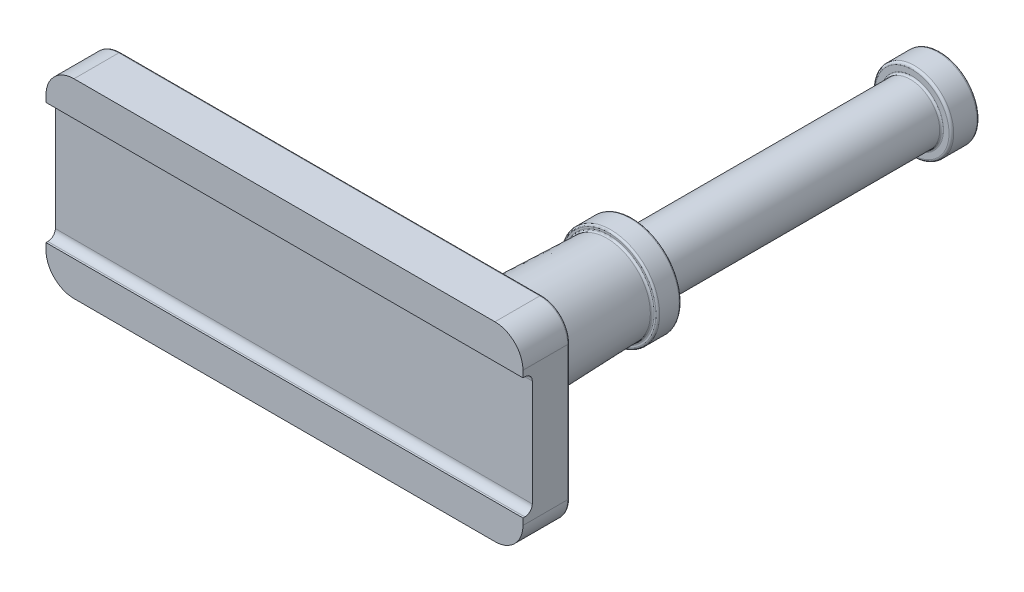
SolidWorks part; units mm, degrees
ref_plane "前视基准面" through (0, 0, 0) normal (0, 0, 1) x (1, 0, 0)
ref_plane "上视基准面" through (0, 0, 0) normal (0, 1, 0) x (1, 0, 0)
ref_plane "右视基准面" through (0, 0, 0) normal (1, 0, 0) x (0, 0, -1)
sketch "Sketch1" plane through (0, 0, 0) normal (0, 0, 1) x (1, 0, 0)
  line L1 (-1277.5, -510) -> (1277.5, -510)
  line L2 (-1277.5, -510) -> (-1277.5, 510)
  line L3 (-1277.5, 510) -> (1277.5, 510)
  line L4 (1277.5, -510) -> (1277.5, 510)
  line L5 (-1277.5, -510) -> (1277.5, 510) construction
  line L6 (-1277.5, 510) -> (1277.5, -510) construction
  point P0 (0, 0)
  dimension "D1" = 2555
  dimension "D2" = 1020
extrude "Extrude1" add sketch "Sketch1" along normal blind 250
fillet "Fillet1" radius 150 4 edges at (1277.5, -510, 125) (-1277.5, -510, 125) (1277.5, 510, 125) (-1277.5, 510, 125)
ref_plane "Plane1" through (762.5, 0, 0) normal (1, 0, 0) x (0, 0, -1)
sketch "Sketch4" plane through (762.5, 0, 0) normal (1, 0, 0) x (0, 0, -1)
  line L0 (0, 0) -> (2500, 0)
  line L1 (0, -360) -> (0, 360) construction
  line L2 (2500, 0) -> (2500, 210)
  line L3 (2500, 210) -> (2350, 210)
  line L4 (2350, 210) -> (2350, 157.5)
  line L5 (2350, 157.5) -> (850, 157.5)
  line L6 (850, 157.5) -> (850, 262.5)
  line L7 (850, 262.5) -> (725, 262.5)
  line L8 (725, 262.5) -> (725, 232.5)
  line L9 (725, 232.5) -> (80, 255.0239)
  line L10 (80, 255.0239) -> (80, 300)
  line L11 (80, 300) -> (0, 300)
  line L12 (0, 300) -> (0, 0)
  line L13 (2500, 0) -> (2810.0618, 0) construction
  dimension "D1" = 2500
  dimension "D2" = 150
  dimension "D3" = 1500
  dimension "D4" = 420
  dimension "D5" = 315
  dimension "D6" = 525
  dimension "D7" = 125
  dimension "D8" = 2
  dimension "D9" = 80
  dimension "D10" = 600
  dimension "D11" = 30
revolve "Revolve1" add sketch "Sketch4" angle 360 about L13
fillet "Fillet2" radius 10 8 edges at (920, 0, -2350) (920, 0, -850) (995, 0, -725) (1025, 0, -725) (1025, 0, -850) (1017.5239, 0, -80) (1062.5, 0, -80) (1062.5, 0, 0)
sketch "Sketch5" plane through (0, 0, 0) normal (0, 0, -1) x (-1, 0, 0)
  line L1 (1127.5, 395) -> (1127.5, 315)
  line L2 (1127.5, 315) -> (1072.5, 260)
  line L3 (1072.5, 260) -> (-290, 260)
  line L4 (-290, 260) -> (-302.5, 272.5)
  line L5 (-302.5, 272.5) -> (-382.5, 272.5)
  line L6 (-382.5, 272.5) -> (-382.5, 222.5)
  line L7 (-382.5, 222.5) -> (-302.5, 222.5)
  line L8 (-302.5, 222.5) -> (-290, 235)
  line L9 (-427.5, 420) -> (-427.5, -420) construction
  line L10 (-1277.5, -360) -> (-1277.5, 360) construction
  line L11 (-290, 235) -> (1072.5, 235)
  line L12 (1127.5, -420) -> (-1127.5, -420)
  line L13 (1187.5, 360) -> (1187.5, -360)
  line L14 (-1127.5, 420) -> (1127.5, 420)
  line L15 (1127.5, -420) -> (-382.5, -420)
  line L16 (1187.5, 360) -> (1187.5, -360)
  line L17 (-382.5, 420) -> (1127.5, 420)
  line L18 (1072.5, 235) -> (1072.5, 95)
  line L19 (1072.5, 95) -> (-290, 95)
  line L20 (-290, 95) -> (-302.5, 107.5)
  line L21 (-302.5, 107.5) -> (-382.5, 107.5)
  line L22 (-382.5, 107.5) -> (-382.5, 57.5)
  line L23 (-382.5, 57.5) -> (-302.5, 57.5)
  line L24 (-302.5, 57.5) -> (-290, 70)
  line L25 (-290, 70) -> (1072.5, 70)
  line L26 (1072.5, 70) -> (1072.5, -70)
  line L27 (1072.5, -70) -> (-290, -70)
  line L28 (-290, -70) -> (-302.5, -57.5)
  line L29 (-302.5, -57.5) -> (-382.5, -57.5)
  line L30 (-382.5, -57.5) -> (-382.5, -107.5)
  line L31 (-382.5, -107.5) -> (-302.5, -107.5)
  line L32 (-302.5, -107.5) -> (-290, -95)
  line L33 (-290, -95) -> (1072.5, -95)
  line L34 (1072.5, -95) -> (1072.5, -235)
  line L35 (1072.5, -235) -> (-290, -235)
  line L36 (-290, -235) -> (-302.5, -222.5)
  line L37 (-302.5, -222.5) -> (-382.5, -222.5)
  line L38 (-382.5, -222.5) -> (-382.5, -272.5)
  line L39 (-382.5, -272.5) -> (-302.5, -272.5)
  line L40 (-302.5, -272.5) -> (-290, -260)
  line L41 (-290, -260) -> (1072.5, -260)
  line L42 (1072.5, -260) -> (1127.5, -315)
  line L43 (1127.5, -315) -> (1127.5, -395)
  line L45 (1127.5, 395) -> (-292.3612, 395)
  line L46 (-292.3612, -395) -> (1127.5, -395)
  arc A0 (-339.8027, -360.7895) -> (-382.5, -420) centre (-382.5, -375) ccw
  arc A1 (-339.8027, -360.7895) -> (-292.3612, -395) centre (-292.3612, -345) ccw
  arc A2 (-292.3612, 395) -> (-339.8027, 360.7895) centre (-292.3612, 345) ccw
  arc A6 (-382.5, 420) -> (-339.8027, 360.7895) centre (-382.5, 375) ccw
  arc A8 (1127.5, -420) -> (1187.5, -360) centre (1127.5, -360) ccw
  arc A9 (1187.5, 360) -> (1127.5, 420) centre (1127.5, 360) ccw
  arc A10 (1127.5, -420) -> (1187.5, -360) centre (1127.5, -360) ccw
  arc A11 (1187.5, 360) -> (1127.5, 420) centre (1127.5, 360) ccw
  dimension "D3" = 90
  dimension "D19" = 100
  dimension "D20" = 100
  dimension "D2" = 850
  dimension "D4" = 45
  dimension "D5" = 45
  dimension "D6" = 45
  dimension "D7" = 45
  dimension "D8" = 45
  dimension "D9" = 45
  dimension "D10" = 45
  dimension "D11" = 45
  dimension "D12" = 45
  dimension "D13" = 45
  dimension "D14" = 25
  dimension "D15" = 45
  dimension "D16" = 25
  dimension "D17" = 50
  dimension "D18" = 80
  dimension "D21" = 25
  dimension "D22" = 140
  dimension "D1" = 90
extrude "Extrude2" cut sketch "Sketch5" against normal blind 150
fillet "Fillet3" radius 20 12 edges at (-1127.5, 315, 75) (-1072.5, 260, 75) (-1072.5, 235, 75) (-1072.5, 95, 75) (-1072.5, 70, 75) (-1072.5, -70, 75) (-1072.5, -95, 75) (-1072.5, -235, 75) (-1072.5, -260, 75) (-1127.5, -315, 75) (-1127.5, 395, 75) (-1127.5, -395, 75)
sketch "Sketch7" plane through (0, 0, 0) normal (0, 0, -1) x (-1, 0, 0)
  line L0 (-557.5, -420) -> (-1127.5, -420)
  line L1 (-1187.5, -360) -> (-1187.5, 360)
  line L2 (-1127.5, 420) -> (-557.5, 420)
  line L3 (-517.5, 380) -> (-517.5, 337.6389)
  line L4 (-517.5, -380) -> (-517.5, -337.6389)
  line L5 (-1277.5, -360) -> (-1277.5, 360) construction
  line L6 (1127.5, -510) -> (-1127.5, -510) construction
  line L7 (-1127.5, 510) -> (1127.5, 510) construction
  arc A0 (-1127.5, -420) -> (-1187.5, -360) centre (-1127.5, -360) cw
  arc A1 (-1187.5, 360) -> (-1127.5, 420) centre (-1127.5, 360) cw
  arc A2 (-578.2595, 303.4476) -> (-578.2595, -303.4476) centre (-762.5, 0) ccw
  arc A6 (-339.8027, -360.7895) -> (-382.5, -420) centre (-382.5, -375) ccw construction
  circle A8 centre (-762.5, 0) radius 310 construction
  arc A9 (-517.5, -337.6389) -> (-578.2595, -303.4476) centre (-557.5, -337.6389) ccw
  arc A10 (-382.5, 420) -> (-339.8027, 360.7895) centre (-382.5, 375) ccw construction
  arc A11 (-557.5, -420) -> (-517.5, -380) centre (-557.5, -380) ccw
  arc A12 (-557.5, 420) -> (-517.5, 380) centre (-557.5, 380) cw
  arc A13 (-517.5, 337.6389) -> (-578.2595, 303.4476) centre (-557.5, 337.6389) cw
  dimension "D6" = 60
  dimension "D7" = 60
  dimension "D8" = 45
  dimension "D9" = 40
  dimension "D1" = 90
  dimension "D2" = 90
  dimension "D3" = 90
  dimension "D4" = 90
  dimension "D5" = 90
extrude "Extrude3" cut sketch "Sketch7" against normal blind 50
fillet "Fillet4" radius 10 90 edges at (-1125.9776, 315.6306, 0) (-1100, 287.5, 0) (-1071.8694, 261.5224, 0) (-387.1079, 260, 0) (296.25, 266.25, 0) (342.5, 272.5, 0) (382.5, 247.5, 0) (342.5, 222.5, 0) (296.25, 228.75, 0) (-381.25, 235, 0) (-1066.6421, 229.1421, 0) (-1072.5, 165, 0) (-1066.6421, 100.8579, 0) (-381.25, 95, 0) (296.25, 101.25, 0) (342.5, 107.5, 0) (382.5, 82.5, 0) (342.5, 57.5, 0) (296.25, 63.75, 0) (-381.25, 70, 0) (-1066.6421, 64.1421, 0) (-1072.5, 0, 0) (-1066.6421, -64.1421, 0) (-381.25, -70, 0) (296.25, -63.75, 0) (342.5, -57.5, 0) (382.5, -82.5, 0) (342.5, -107.5, 0) (296.25, -101.25, 0) (-381.25, -95, 0) (-1066.6421, -100.8579, 0) (-1072.5, -165, 0) (-1066.6421, -229.1421, 0) (-381.25, -235, 0) (296.25, -228.75, 0) (342.5, -222.5, 0) (382.5, -247.5, 0) (342.5, -272.5, 0) (296.25, -266.25, 0) (-387.1079, -260, 0) (-1071.8694, -261.5224, 0) (-1100, -287.5, 0) (-1125.9776, -315.6306, 0) (-1127.5, -349.1421, 0) (-1121.6421, -389.1421, 0) (-407.5694, -395, 0) (321.6061, -385.5554, 0) (418.9998, -348.6796, 0) (-372.5, -420, 0) (-1169.9264, -402.4264, 0) (-1187.5, 0, 0) (-1169.9264, 402.4264, 0) (-372.5, 420, 0) (418.9998, 348.6796, 0) (321.6061, 385.5554, 0) (-407.5694, 395, 0) (-1121.6421, 389.1421, 0) (-1127.5, 349.1421, 0) (1233.566, 466.066, 0) (0, 510, 0) (-1233.566, 466.066, 0) (-1277.5, 0, 0) (-1233.566, -466.066, 0) (0, -510, 0) (1233.566, -466.066, 0) (1277.5, 0, 0) (842.5, -420, 0) (529.2157, -408.2843, 0) (517.5, -358.8194, 0) (537.8834, -302.7793, 0) (1117.5, 0, 0) (537.8834, 302.7793, 0) (517.5, 358.8194, 0) (529.2157, 408.2843, 0) (842.5, 420, 0) (1169.9264, 402.4264, 0) (1187.5, 0, 0) (1169.9264, -402.4264, 0) (1187.5, 0, 50) (1169.9264, 402.4264, 50) (842.5, 420, 50) (529.2157, 408.2843, 50) (517.5, 358.8194, 50) (537.8834, 302.7793, 50) (1117.5, 0, 50) (537.8834, -302.7793, 50) (517.5, -358.8194, 50) (529.2157, -408.2843, 50) (842.5, -420, 50) (1169.9264, -402.4264, 50)
sketch "Sketch8" plane through (1277.5, 0, 0) normal (1, 0, 0) x (0, 0, -1)
  line L0 (0, 0) -> (-355.8382, 0) construction
  line L1 (0, 360) -> (0, -360) construction
  line L2 (-250, 325) -> (-240, 325)
  line L3 (-250, -360) -> (-250, 360) construction
  line L4 (-200, 285) -> (-200, -285)
  line L5 (-240, -325) -> (-250, -325)
  line L6 (-250, -325) -> (-250, 325)
  arc A0 (-240, 325) -> (-200, 285) centre (-240, 285) cw
  arc A1 (-200, -285) -> (-240, -325) centre (-240, -285) cw
  dimension "D3" = 40
  dimension "D4" = 40
  dimension "D1" = 650
  dimension "D2" = 50
extrude "Extrude4" cut sketch "Sketch8" against normal through all
scale "Scale1" bodies to scale 110 scale about centroid uniform scaling yes scale factor 0.8
fillet "Fillet5" radius 10 2 edges at (839.3404, 0, -1941.0003) (839.3404, 0, -2061.0003)
